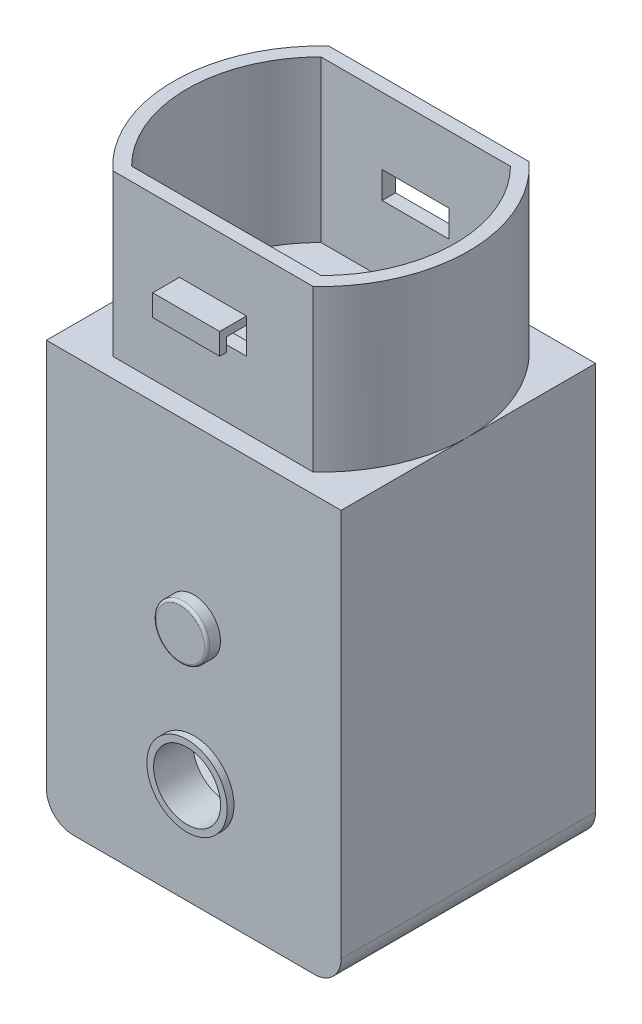
SolidWorks part; units mm, degrees
ref_plane "Front Plane" through (0, 0, 0) normal (0, 0, 1) x (1, 0, 0)
ref_plane "Top Plane" through (0, 0, 0) normal (0, 1, 0) x (1, 0, 0)
ref_plane "Right Plane" through (0, 0, 0) normal (1, 0, 0) x (0, 0, -1)
sketch "Sketch2" plane through (0, 0, 0) normal (0, 0, 1) x (1, 0, 0)
  line L1 (-11, 15.5) -> (11, 15.5)
  line L2 (-11, 15.5) -> (-11, -13.5)
  line L3 (-9, -15.5) -> (9, -15.5)
  line L4 (11, 15.5) -> (11, -13.5)
  line L5 (-11, 15.5) -> (11, -15.5) construction
  line L6 (-11, -15.5) -> (11, 15.5) construction
  arc A0 (-9, -15.5) -> (-11, -13.5) centre (-9, -13.5) cw
  arc A1 (9, -15.5) -> (11, -13.5) centre (9, -13.5) ccw
  point P0 (0, 0)
  dimension "D3" = 2
  dimension "D1" = 31
  dimension "D2" = 22
extrude "Boss-Extrude1" add sketch "Sketch2" along normal mid plane 19
sketch "Sketch3" plane through (0, 0, 0) normal (0, 0, 1) x (1, 0, 0)
  line L0 (0, -15.5135) -> (0, -20.5135) construction
  line L1 (-2, -20.5135) -> (2, -20.5135)
  line L2 (2, -20.5135) -> (2, -15.5135)
  line L3 (2, -15.5135) -> (-2, -15.5135)
  line L4 (-2, -15.5135) -> (-2, -20.5135)
  circle A0 centre (0, -18.0135) radius 1.5682
  dimension "D2" = 2
  dimension "D3" = 4
extrude "Boss-Extrude2" add sketch "Sketch3" along normal mid plane 1 separate body
sketch "Sketch4" plane through (0, 15.5, 0) normal (0, 1, 0) x (1, 0, 0)
  line L0 (-7.4796, 8.0657) -> (7.4796, 8.0657)
  line L1 (-7.0764, 7.0657) -> (7.0764, 7.0657)
  line L2 (7.4796, -8.0657) -> (-7.4796, -8.0657)
  line L3 (7.0764, -7.0657) -> (-7.0764, -7.0657)
  arc A0 (-7.4796, 8.0657) -> (-7.4796, -8.0657) centre (0, 0) ccw
  arc A1 (7.4796, -8.0657) -> (7.4796, 8.0657) centre (0, 0) ccw
  arc A2 (7.0764, -7.0657) -> (7.0764, 7.0657) centre (0, 0) ccw
  arc A3 (-7.0764, 7.0657) -> (-7.0764, -7.0657) centre (0, 0) ccw
  dimension "D1" = 1
extrude "Boss-Extrude3" add sketch "Sketch4" along normal blind 12
sketch "Sketch5" plane through (0, 0, -8.0657) normal (0, 0, -1) x (-1, 0, 0)
  line L0 (0, 15.5) -> (0, 27.5) construction
  line L1 (-7.4796, 15.5) -> (7.4796, 15.5) construction
  line L2 (-7.4796, 27.5) -> (7.4796, 27.5) construction
  line L4 (-2.5, 22.5) -> (2.5, 22.5)
  line L5 (-2.5, 22.5) -> (-2.5, 20.5)
  line L6 (-2.5, 20.5) -> (2.5, 20.5)
  line L7 (2.5, 22.5) -> (2.5, 20.5)
  line L8 (-2.5, 22.5) -> (2.5, 20.5) construction
  line L9 (-2.5, 20.5) -> (2.5, 22.5) construction
  point P6 (0, 21.5)
  dimension "D1" = 2
  dimension "D2" = 5
extrude "Cut-Extrude1" cut sketch "Sketch5" against normal through all
sketch "Sketch6" plane through (0, 0, 9.5) normal (0, 0, 1) x (1, 0, 0)
  line L0 (0, -15.5) -> (0, 15.5) construction
  line L1 (-9, -15.5) -> (9, -15.5) construction
  line L2 (11, 15.5) -> (-11, 15.5) construction
  circle A0 centre (0, -7.5643) radius 2.5
  dimension "D1" = 5
extrude "Cut-Extrude2" cut sketch "Sketch6" against normal through all
sketch "Sketch7" plane through (0, 0, 9.5) normal (0, 0, 1) x (1, 0, 0)
  circle A0 centre (0, -7.5643) radius 3
  circle A1 centre (0, -7.5643) radius 2.5
  dimension "D1" = 6
extrude "Boss-Extrude4" add sketch "Sketch7" along normal blind 0.5
sketch "Sketch8" plane through (0, 0, 9.5) normal (0, 0, 1) x (1, 0, 0)
  line L0 (0, 15.5) -> (0, -4.5643) construction
  line L1 (11, 15.5) -> (-11, 15.5) construction
  circle A0 centre (0, -7.5643) radius 3 construction
  circle A1 centre (0, 2.5444) radius 2
  dimension "D1" = 4
extrude "Boss-Extrude5" add sketch "Sketch8" along normal blind 1
fillet "Fillet1" radius 0.2 1 edges at (2, 2.5444, 10.5)
sketch "Sketch9" plane through (0, 15.5, 0) normal (0, 1, 0) x (1, 0, 0)
  line L0 (7.0764, 7.0657) -> (-7.0764, 7.0657) construction
  line L1 (-7.0764, -7.0657) -> (7.0764, -7.0657) construction
  line L2 (7.0764, 7.0657) -> (-7.0764, 7.0657)
  line L3 (-7.0764, -7.0657) -> (7.0764, -7.0657)
  arc A0 (-7.0764, 7.0657) -> (-7.0764, -7.0657) centre (0, 0) ccw construction
  arc A1 (7.0764, -7.0657) -> (7.0764, 7.0657) centre (0, 0) ccw construction
  arc A2 (-7.0764, 7.0657) -> (-7.0764, -7.0657) centre (0, 0) ccw
  arc A3 (7.0764, -7.0657) -> (7.0764, 7.0657) centre (0, 0) ccw
extrude "Cut-Extrude3" cut sketch "Sketch9" against normal blind 28
sketch "Sketch10" plane through (0, 15.5, 0) normal (0, 1, 0) x (1, 0, 0)
  line L0 (7.4796, 8.0657) -> (-7.4796, 8.0657) construction
  line L1 (-7.4796, -8.0657) -> (7.4796, -8.0657) construction
  line L2 (7.4796, 8.0657) -> (-7.4796, 8.0657)
  line L3 (-7.4796, -8.0657) -> (7.4796, -8.0657)
  arc A0 (-7.4796, 8.0657) -> (-11, 0) centre (0, 0) ccw construction
  arc A1 (11, 0) -> (7.4796, 8.0657) centre (0, 0) ccw construction
  arc A2 (7.4796, -8.0657) -> (11, 0) centre (0, 0) ccw construction
  arc A3 (-11, 0) -> (-7.4796, -8.0657) centre (0, 0) ccw construction
  arc A4 (-7.4796, 8.0657) -> (-11, 0) centre (0, 0) ccw
  arc A5 (11, 0) -> (7.4796, 8.0657) centre (0, 0) ccw
  arc A6 (7.4796, -8.0657) -> (11, 0) centre (0, 0) ccw
  arc A7 (-11, 0) -> (-7.4796, -8.0657) centre (0, 0) ccw
  circle A8 centre (0, 0) radius 3.5436
extrude "Boss-Extrude6" add sketch "Sketch10" against normal blind 1
sketch "Sketch11" plane through (0, 0, -8.0657) normal (0, 0, -1) x (-1, 0, 0)
  line L0 (-2.5, 22.5) -> (-2.5, 23.1)
  line L1 (-2.5, 23.1) -> (2.5, 23.1)
  line L2 (2.5, 23.1) -> (2.5, 22.5)
  line L3 (2.5, 22.5) -> (-2.5, 22.5)
  dimension "D1" = 0.6
extrude "Boss-Extrude7" add sketch "Sketch11" along normal blind 2
sketch "Sketch12" plane through (0, 22.5, 0) normal (0, -1, 0) x (1, 0, 0)
  line L0 (2.5, -10.0657) -> (-2.5, -10.0657)
  line L1 (-2.5, -10.0657) -> (-2.5, -9.5657)
  line L2 (-2.5, -10.0657) -> (-2.5, -8.0657) construction
  line L3 (-2.5, -9.5657) -> (2.5, -9.5657)
  line L4 (2.5, -10.0657) -> (2.5, -8.0657) construction
  line L5 (2.5, -9.5657) -> (2.5, -10.0657)
  dimension "D1" = 0.5
extrude "Boss-Extrude8" add sketch "Sketch12" along normal blind 1
mirror "Mirror1" about plane through (0, 0, 0) normal (0, 0, 1) of "Boss-Extrude8", "Boss-Extrude7"
